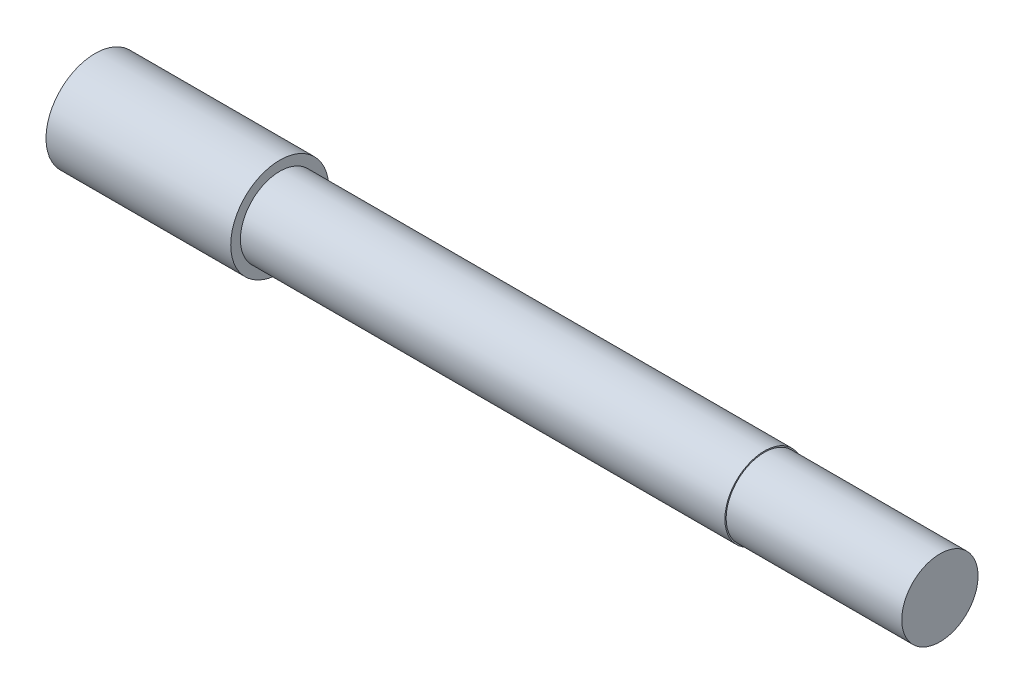
SolidWorks part; units mm, degrees
ref_plane "Plan de face" through (0, 0, 0) normal (0, 0, 1) x (1, 0, 0)
ref_plane "Plan de dessus" through (0, 0, 0) normal (0, 1, 0) x (1, 0, 0)
ref_plane "Plan de droite" through (0, 0, 0) normal (1, 0, 0) x (0, 0, -1)
sketch "Esquisse1" plane through (0, 0, 0) normal (0, 0, 1) x (1, 0, 0)
  line L0 (0, 0) -> (144.2979, 0) construction
  line L1 (0, 0) -> (0, 8.1)
  line L2 (0, 8.1) -> (30.5, 8.1)
  line L3 (30.5, 8.1) -> (30.5, 6.5)
  line L4 (30.5, 6.5) -> (110.5, 6.5)
  line L5 (110.5, 6.5) -> (110.5, 6.3)
  line L6 (110.5, 6.3) -> (139.5, 6.3)
  line L7 (139.5, 6.3) -> (139.5, 0)
  line L8 (0, 0) -> (139.5, 0)
  dimension "D1" = 16.2
  dimension "D2" = 13
  dimension "D3" = 30.5
  dimension "D4" = 109
  dimension "D5" = 29
  dimension "D6" = 12.6
revolve "Révolution1" add sketch "Esquisse1" angle 360 about L0
